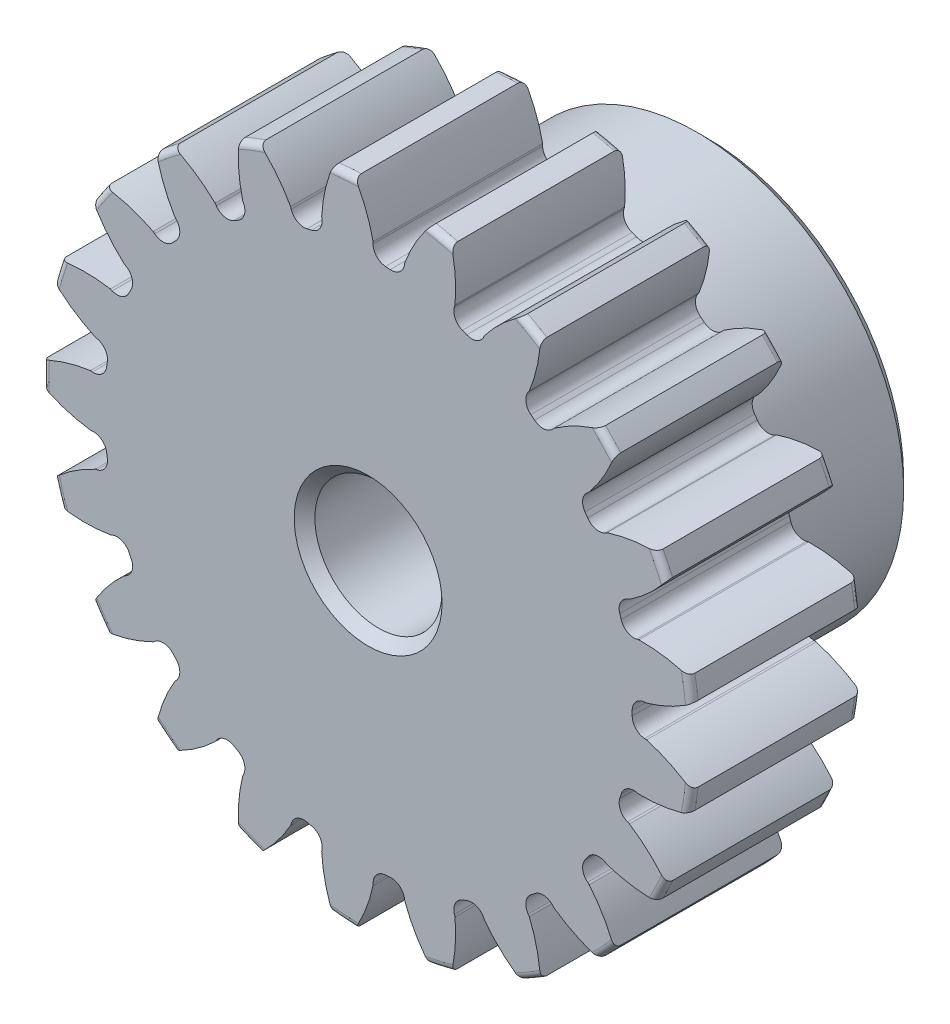
SolidWorks part; units mm, degrees
ref_plane "Front" through (0, 0, 0) normal (0, 0, 1) x (1, 0, 0)
ref_plane "Top" through (0, 0, 0) normal (0, 1, 0) x (1, 0, 0)
ref_plane "Right" through (0, 0, 0) normal (1, 0, 0) x (0, 0, -1)
sketch "Sketch1" plane through (0, 0, 0) normal (0, 0, 1) x (1, 0, 0)
  line L0 (-266.7, 0) -> (266.7, 0) construction
  circle A0 centre (0, 0) radius 12.192
  circle A1 centre (0, 0) radius 11.1125 construction
  circle A3 centre (0, 0) radius 9.888 construction
  dimension "D1" = 1.2245
  dimension "OD" = 24.384
  dimension "Ptich Dia" = 22.225
  dimension "D2" = 2.304
  dimension "Root Dia" = 19.776
  dimension "D3" = 1.0795
  dimension "Number of Teeth" = 533.4
extrude "Boss-Extrude1" add sketch "Sketch1" against normal blind 6.35
sketch "Sketch2" plane through (0, 0, 0) normal (1, 0, 0) x (0, 0, -1)
  line L0 (6.35, 0) -> (12.7, 0)
  line L1 (6.35, 0) -> (6.35, 7.7391)
  line L2 (6.35, 7.7391) -> (12.7, 7.7391)
  line L3 (12.7, 7.7391) -> (12.7, 0)
  point P5 (12.7, -7.7391)
  point P6 (0, -12.192)
  point P7 (6.35, -12.192)
  point P9 (0, 12.192)
  dimension "Face Wd" = 6.35
  dimension "B Hub Dia" = 15.4781
  dimension "D O'all Lg." = 12.7
revolve "Revolve1" add sketch "Sketch2" angle 360 about L0
fillet "Fillet2" radius 0.2438 3 edges at (12.192, 0, -6.35) (12.192, 0, 0) (7.7391, 0, -6.35)
sketch "Sketch3" plane through (0, 0, 0) normal (0, 0, 1) x (1, 0, 0)
  line L0 (0, 0) -> (0, 12.192) construction
  line L1 (-3.5715, 9.8126) -> (0, 11.1125)
  line L2 (-9.5921, 11.1125) -> (9.5921, 11.1125) construction
  line L3 (-9.0136, 7.8318) -> (9.0136, 14.3932) construction
  line L4 (-3.5715, 9.8126) -> (0, 0) construction
  line L5 (-8.7072, 5.7644) -> (0, 0) construction
  line L6 (-8.7072, 5.7644) -> (-2.9375, 14.4795) construction
  line L7 (-2.4809, 10.1433) -> (0, 0) construction
  line L8 (-2.4809, 10.1433) -> (0.1034, 10.7754) construction
  arc A0 (-3.5715, 9.8126) -> (-8.7072, 5.7644) centre (0, 0) ccw
  circle A1 centre (0, 0) radius 11.1125 construction
  circle A2 centre (0, 0) radius 10.4423 construction
  arc A3 (-3.5715, 9.8126) -> (-2.4809, 10.1433) centre (0, 0) cw
  circle A4 centre (0, 0) radius 12.192 construction
  point P6 (0, 11.1125)
  dimension "D1" = 3.8007
  dimension "Pressure Angle" = 20
  dimension "D2" = 6.6512
  dimension "D3" = 10.4519
  dimension "D4" = 1.1402
  dimension "D5" = 2.6605
sketch "Sketch4" plane through (0, 0, 0) normal (0, 0, 1) x (1, 0, 0)
  line L0 (0, 0) -> (0.8281, 11.0504) construction
  line L1 (0.1845, 10.4407) -> (0.1845, 9.8863)
  line L2 (0, 11.1125) -> (1.6562, 10.9884) construction
  line L3 (1.3737, 10.3516) -> (1.2911, 9.8034)
  line L4 (0.1845, 9.8863) -> (0, 0) construction
  line L5 (0, 0) -> (0, 12.192) construction
  line L6 (-8.7072, 5.7644) -> (-2.9375, 14.4795) construction
  line L7 (-8.7072, 5.7644) -> (-2.9375, 14.4795) construction
  arc A0 (1.2911, 9.8034) -> (0.1845, 9.8863) centre (0, 0) ccw
  arc A1 (0, 11.1125) -> (1.6562, 10.9884) centre (0, 0) cw construction
  circle A2 centre (0, 0) radius 11.1125 construction
  circle A3 centre (0, 0) radius 10.4423 construction
  circle A4 centre (0, 0) radius 9.888 construction
  arc A5 (5.0628, 13.88) -> (-2.9375, 14.4795) centre (0, 0) ccw
  spline S0 degree 2 poles (-2.9375, 14.4795) (-0.3513, 12.9712) (0.1845, 10.4407) knots 0 0 0 1 1 1
  spline S1 degree 2 poles (5.0628, 13.88) (2.2806, 12.774) (1.3737, 10.3516) knots 0 0 0 1 1 1
  dimension "D1" = 1.6624
extrude "Cut-Extrude1" cut sketch "Sketch4" against normal through all
fillet "Fillet1" radius 0.4987 2 edges at (1.2911, 9.8034, -3.175) (0.1845, 9.8863, -3.175)
pattern_circular "CirPattern1" count 21 over 360 about axis through (0, 0, -6.35) along (0, 0, 1) of "Cut-Extrude1", "Fillet1"
sketch "Sketch5" plane through (0, 0, 0) normal (0, 0, 1) x (1, 0, 0)
  circle A0 centre (0, 0) radius 2.3813
  circle A1 centre (0, 0) radius 2.3813 construction
  dimension "Bore Min" = 4.7625
  dimension "Bore Max" = 4.7625
extrude "Cut-Extrude2" cut sketch "Sketch5" against normal through all
chamfer "Chamfer1" distance 0.387 angle 45 3 edges at (7.7391, 0, -12.7) (2.3813, 0, 0) (2.3813, 0, -12.7)
sketch "Pitch Dia" plane through (0, 0, 0) normal (0, 0, 1) x (1, 0, 0)
  circle A0 centre (0, 0) radius 11.1125 construction
  circle A1 centre (0, 0) radius 11.1125 construction
equation "\"D1@Boss-Extrude1\" = \"Face Wd@Sketch2\""
equation "\"D2@Sketch3\" = \"D1@Sketch3\"*1.75"
equation "\"D3@Sketch3\" = \"D1@Sketch3\"+\"D2@Sketch3\""
equation "\"D4@Sketch3\" = \"D1@Sketch3\"*.3"
equation "\"D5@Sketch3\" = \"D1@Sketch3\"-\"D4@Sketch3\""
equation "\"D1@Sketch4\" = 1.5708/(\"Number of Teeth@Sketch1\"/\"Ptich Dia@Sketch1\")"
equation "\"D1@Chamfer1\" = \"B Hub Dia@Sketch2\"*.025"
equation "\"D1@CirPattern1\" = \"Number of Teeth@Sketch1\""
equation "\"D1@Fillet1\" = \"D1@Sketch4\"*.3"
equation "\"D1@Fillet2\" = \"OD@Sketch1\"*.01"
equation "\"D1@Sketch1\" = 1.157/(\"Number of Teeth@Sketch1\"/\"Ptich Dia@Sketch1\")"
